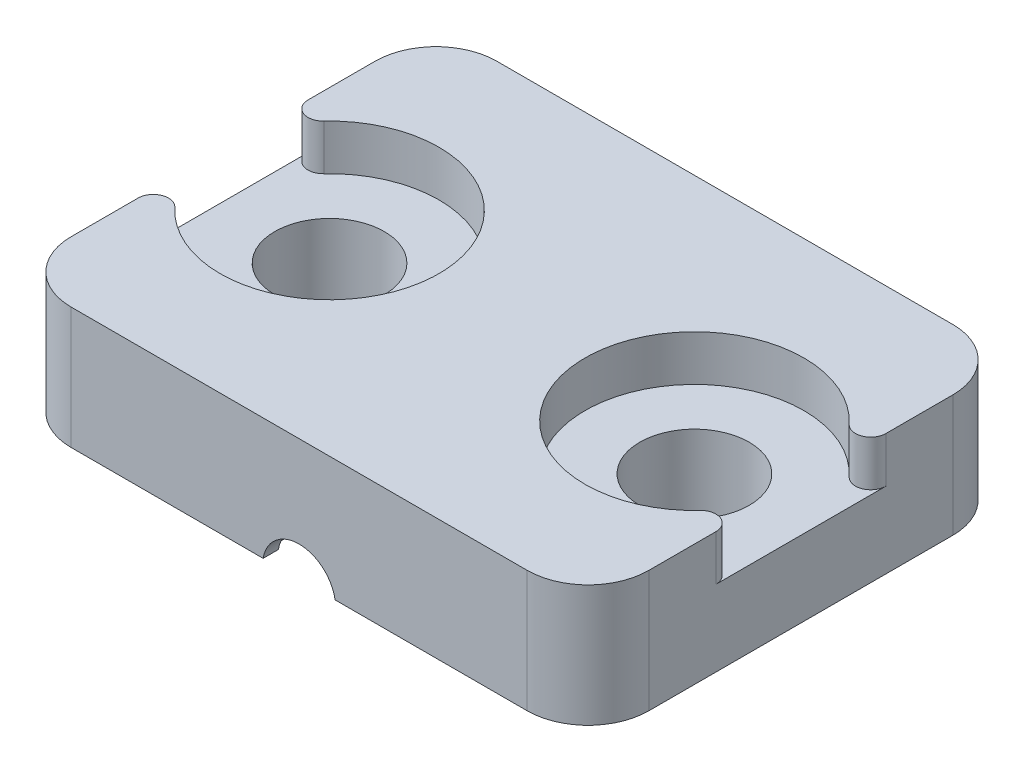
SolidWorks part; units mm, degrees
ref_plane "Front Plane" through (0, 0, 0) normal (0, 0, 1) x (1, 0, 0)
ref_plane "Top Plane" through (0, 0, 0) normal (0, 1, 0) x (1, 0, 0)
ref_plane "Right Plane" through (0, 0, 0) normal (1, 0, 0) x (0, 0, -1)
sketch "Sketch1" plane through (0, 0, 0) normal (0, 1, 0) x (1, 0, 0)
  line L0 (0, 8.89) -> (0, -8.89) construction
  line L1 (12.065, -8.89) -> (-12.065, -8.89)
  line L2 (12.065, -8.89) -> (12.065, 8.89)
  line L3 (12.065, 8.89) -> (-12.065, 8.89)
  line L4 (-12.065, -8.89) -> (-12.065, 8.89)
  line L5 (12.065, -8.89) -> (-12.065, 8.89) construction
  line L6 (12.065, 8.89) -> (-12.065, -8.89) construction
  circle A0 centre (-7.62, 0) radius 2.286
  circle A1 centre (7.62, 0) radius 2.286
  point P0 (0, 0)
  dimension "D1" = 4.572
  dimension "D2" = 17.78
  dimension "D3" = 24.13
  dimension "D4" = 7.62
extrude "Boss-Extrude1" add sketch "Sketch1" along normal blind 5.08
sketch "Sketch2" plane through (0, 0, 8.89) normal (0, 0, 1) x (1, 0, 0)
  line L0 (-12.065, 0) -> (12.065, 0) construction
  circle A0 centre (0, -0.254) radius 1.778
  dimension "D2" = 3.556
  dimension "D1" = 0.254
extrude "Cut-Extrude1" cut sketch "Sketch2" against normal through all
sketch "Sketch4" plane through (0, 0, 8.89) normal (0, 0, 1) x (1, 0, 0)
  line L0 (-1.7598, 0) -> (-1.5027, 0)
  line L1 (1.7598, 0) -> (12.065, 0) construction
  line L2 (1.5027, 0) -> (1.7598, 0)
  arc A1 (1.7598, 0) -> (-1.7598, 0) centre (0, -0.254) ccw
  circle A2 centre (0, -0.254) radius 1.524
  dimension "D1" = 0.254
extrude "Boss-Extrude2" add sketch "Sketch4" against normal blind 0.635
pattern_linear "LPattern1" count 10 spacing 1.905 along (0, 0, -1) of "Boss-Extrude2"
sketch "Sketch5" plane through (0, 5.08, 0) normal (0, 1, 0) x (1, 0, 0)
  circle A0 centre (-7.62, 0) radius 4.572
  circle A1 centre (7.62, 0) radius 4.572
  dimension "D1" = 9.144
extrude "Cut-Extrude2" cut sketch "Sketch5" against normal blind 1.905
fillet "Fillet1" radius 0.635 4 edges at (12.065, 4.1275, 1.0701) (12.065, 4.1275, -1.0701) (-12.065, 4.1275, -1.0701) (-12.065, 4.1275, 1.0701)
fillet "Fillet2" radius 2.54 4 edges at (12.065, 2.54, 8.89) (12.065, 2.54, -8.89) (-12.065, 2.54, -8.89) (-12.065, 2.54, 8.89)
sketch "Sketch6" plane through (0, 0, 0) normal (0, 0, 1) x (1, 0, 0)
  circle A0 centre (0, 0) radius 3.81
  dimension "D1" = 7.62
extrude "Cut-Extrude3" cut sketch "Sketch6" along normal mid plane 5.08
